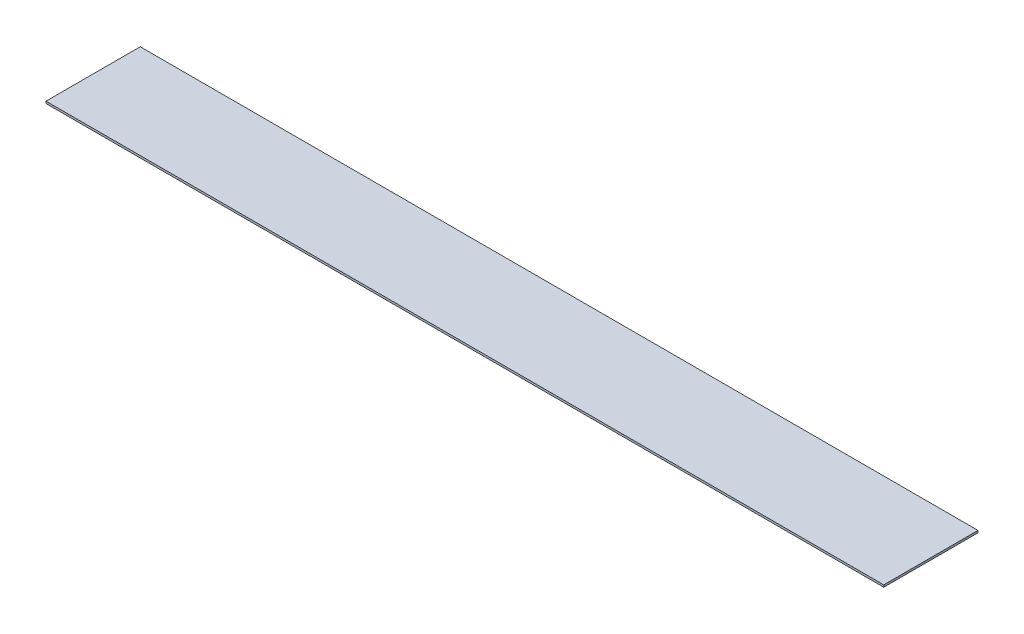
SolidWorks part; units mm, degrees
material "Maple"
ref_plane "Front Plane" through (0, 0, 0) normal (0, 0, 1) x (1, 0, 0)
ref_plane "Top Plane" through (0, 0, 0) normal (0, 1, 0) x (1, 0, 0)
ref_plane "Right Plane" through (0, 0, 0) normal (1, 0, 0) x (0, 0, -1)
sketch "Sketch1" plane through (0, 0, 0) normal (0, 1, 0) x (1, 0, 0)
  line L1 (-2000, 225) -> (2000, 225)
  line L2 (-2000, 225) -> (-2000, -225)
  line L3 (-2000, -225) -> (2000, -225)
  line L4 (2000, 225) -> (2000, -225)
  line L5 (-2000, 225) -> (2000, -225) construction
  line L6 (-2000, -225) -> (2000, 225) construction
  point P0 (0, 0)
  dimension "D1" = 4000
  dimension "D2" = 450
extrude "Boss-Extrude1" add sketch "Sketch1" along normal blind 10
